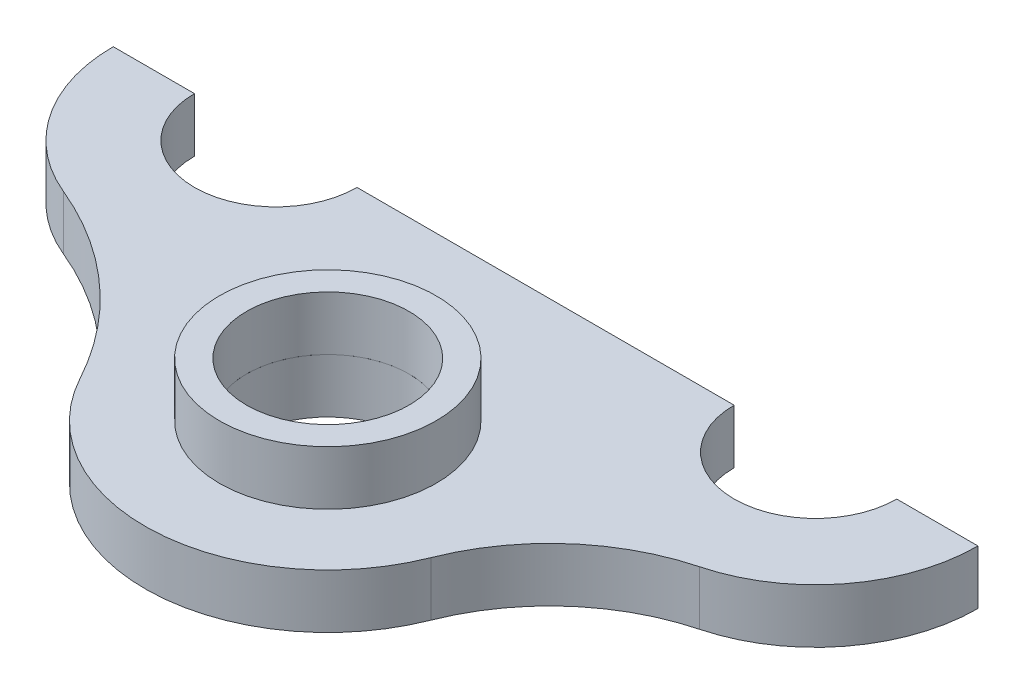
SolidWorks part; units mm, degrees
ref_plane "Front Plane" through (0, 0, 0) normal (0, 0, 1) x (1, 0, 0)
ref_plane "Top Plane" through (0, 0, 0) normal (0, 1, 0) x (1, 0, 0)
ref_plane "Right Plane" through (0, 0, 0) normal (1, 0, 0) x (0, 0, -1)
sketch "Sketch1" plane through (0, 0, 0) normal (0, 1, 0) x (1, 0, 0)
  line L0 (-6.35, 4.7625) -> (9.398, 4.7621)
  circle A0 centre (-6.35, 0) radius 2.3813
  circle A1 centre (9.4615, 0) radius 2.3813
  circle A2 centre (-6.35, 0) radius 4.7625
  circle A3 centre (9.4615, 0) radius 4.7625
  circle A4 centre (1.524, -6.35) radius 2.3812
  circle A5 centre (1.524, -6.35) radius 5.353
  arc A6 (-8.1764, -4.3984) -> (-3.1815, -8.9019) centre (-12.0416, -13.707) cw
  arc A7 (6.5046, -8.3115) -> (10.6745, -4.6054) centre (12.2461, -10.5726) cw
  dimension "D1" = 4.7625
  dimension "D2" = 6.35
  dimension "D3" = 0
  dimension "D5" = 4.7625
  dimension "D6" = 9.525
  dimension "D7" = 9.525
  dimension "D8" = 4.7625
  dimension "D9" = 7.874
  dimension "D10" = 6.35
  dimension "D4" = 15.8115
extrude "Boss-Extrude1" add sketch "Sketch1" along normal blind 1.5875 contours A2 A0 | A2 A6 A5 | A5 A3 L0 A2 | A3 A1 | A5 A7 A3 | A5 A4
sketch "Sketch2" plane through (0, 0, 0) normal (0, -1, 0) x (1, 0, 0)
  circle A0 centre (1.524, 6.35) radius 3.175
  dimension "D1" = 6.35
extrude "Boss-Extrude2" add sketch "Sketch2" along normal blind 1.5875
sketch "Sketch3" plane through (0, 0, 0) normal (0, 1, 0) x (1, 0, 0)
  circle A0 centre (1.524, -6.35) radius 2.3812
extrude "Boss-Extrude3" add sketch "Sketch3" along normal blind 19.05
sketch "Sketch4" plane through (0, 19.05, 0) normal (0, 1, 0) x (1, 0, 0)
  circle A0 centre (1.524, -6.35) radius 3.175
  dimension "D1" = 6.35
extrude "Boss-Extrude4" add sketch "Sketch4" against normal blind 1.5875
sketch "Sketch5" plane through (0, 17.4625, 0) normal (0, -1, 0) x (1, 0, 0)
  line L0 (-6.35, -4.7625) -> (9.4615, -4.7625)
  circle A0 centre (-6.35, 0) radius 2.3813
  circle A1 centre (9.4615, 0) radius 2.3813
  circle A2 centre (1.524, 6.35) radius 5.353
  circle A3 centre (-6.35, 0) radius 4.7625
  circle A4 centre (9.4615, 0) radius 4.7625
  arc A5 (-8.1764, 4.3984) -> (-3.1815, 8.9019) centre (-12.0416, 13.707) ccw
  arc A6 (6.5046, 8.3115) -> (10.6745, 4.6054) centre (12.2461, 10.5726) ccw
  circle M1 centre (1.524, 6.35) radius 2.3812
  circle M2 centre (1.524, 6.35) radius 3.175
extrude "Boss-Extrude5" add sketch "Sketch5" along normal blind 1.5875 separate body contours A2 M2 | A6 A2 A4 | A4 A1 | A5 A3 A2 | A4 A2 A3 L0 | A3 A0 | M2 M1
sketch "Sketch6" plane through (0, 19.05, 0) normal (0, 1, 0) x (1, 0, 0)
  circle A0 centre (1.524, -6.35) radius 2.3813
  dimension "D1" = 4.7625
extrude "Cut-Extrude1" cut sketch "Sketch6" against normal through all
sketch "Sketch7" plane through (0, 1.5875, 0) normal (0, 1, 0) x (1, 0, 0)
  line L1 (20.3943, 5.8739) -> (-20.2966, 5.8739)
  line L2 (20.3943, 5.8739) -> (20.3943, -14.1314)
  line L3 (20.3943, -14.1314) -> (-20.2966, -14.1314)
  line L4 (-20.2966, 5.8739) -> (-20.2966, -14.1314)
extrude "Cut-Extrude2" cut sketch "Sketch7" against normal through all
sketch "Sketch8" plane through (0, 17.4625, 0) normal (0, 1, 0) x (1, 0, 0)
  line L0 (-11.1125, 0) -> (14.224, 0)
  line L1 (14.224, 0) -> (14.224, 6.4373)
  line L2 (14.224, 6.4373) -> (-11.1125, 6.4373)
  line L3 (-11.1125, 6.4373) -> (-11.1125, 0)
  line L4 (-11.1125, 0) -> (-11.118, -0.0459)
  line L5 (-11.118, -0.0459) -> (-11.118, -13.7921)
  line L6 (-11.118, -13.7921) -> (14.224, -13.7921)
  line L7 (14.224, -13.7921) -> (14.224, 0)
  line L8 (14.224, 0) -> (14.2295, -0.0215)
  arc A0 (-6.35, 4.7625) -> (-8.1764, -4.3984) centre (-6.35, 0) ccw construction
  arc A1 (10.6745, -4.6054) -> (9.4615, 4.7625) centre (9.4615, 0) ccw construction
  arc M4 (10.6745, -4.6054) -> (9.4615, 4.7625) centre (9.4615, 0) ccw
  line M5 (9.4615, 4.7625) -> (-6.35, 4.7625)
  arc M6 (-6.35, 4.7625) -> (-8.1764, -4.3984) centre (-6.35, 0) ccw
  circle M8 centre (9.4615, 0) radius 2.3813
  circle M9 centre (-6.35, 0) radius 2.3813
extrude "Cut-Extrude3" cut sketch "Sketch8" against normal through all contours L0 M6 M9 M8 M4 M5
